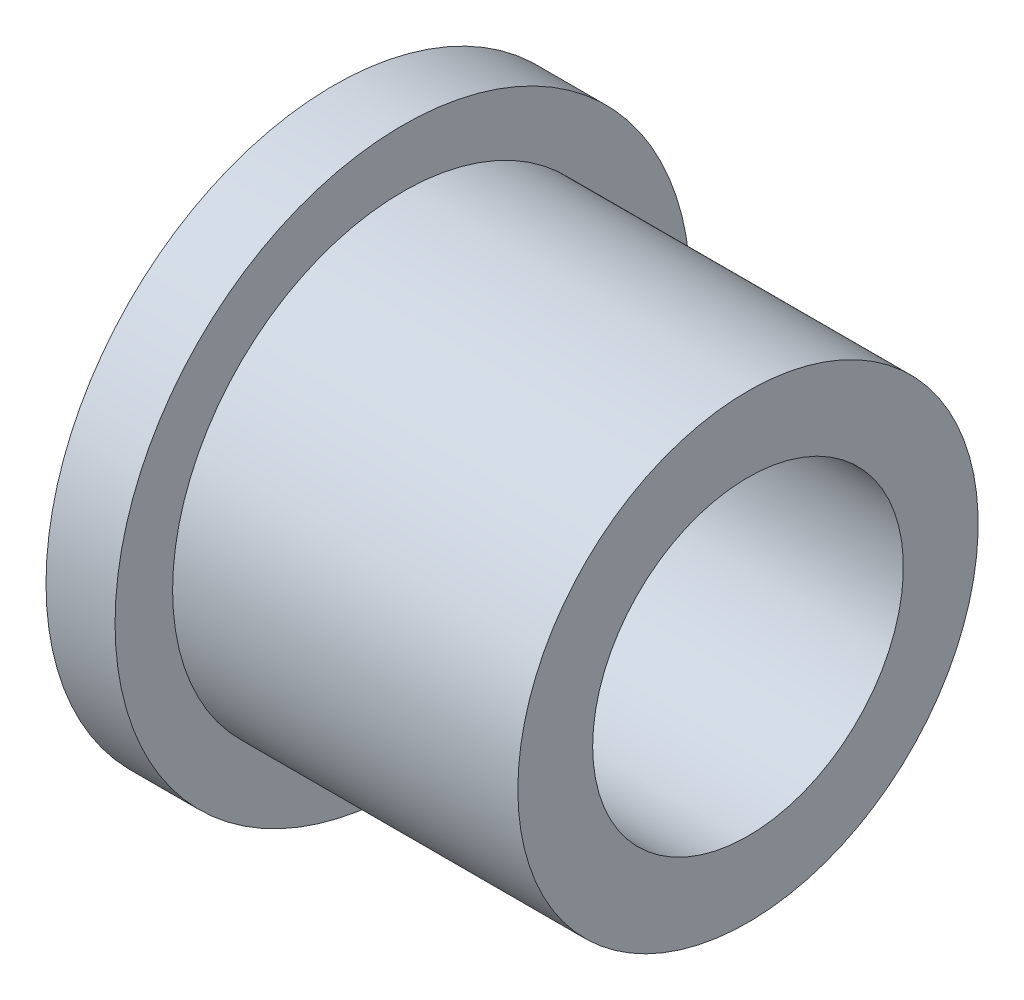
SolidWorks part; units mm, degrees
ref_plane "Front Plane" through (0, 0, 0) normal (0, 0, 1) x (1, 0, 0)
ref_plane "Top Plane" through (0, 0, 0) normal (0, 1, 0) x (1, 0, 0)
ref_plane "Right Plane" through (0, 0, 0) normal (1, 0, 0) x (0, 0, -1)
sketch "Sketch1" plane through (0, 0, 0) normal (0, 0, 1) x (1, 0, 0)
  line L0 (0, -16.586) -> (0, 16.586) construction
  line L1 (-30.377, 0) -> (30.377, 0) construction
  line L2 (0, 8.5725) -> (0, 12.7)
  line L3 (0, 12.7) -> (-19.05, 12.7)
  line L4 (-19.05, 12.7) -> (-19.05, 15.875)
  line L5 (-19.05, 15.875) -> (-22.86, 15.875)
  line L6 (-22.86, 15.875) -> (-22.86, 8.5725)
  line L7 (-22.86, 8.5725) -> (0, 8.5725)
  dimension "D1" = 19.05
  dimension "D2" = 22.86
  dimension "D3" = 17.145
  dimension "D4" = 31.75
  dimension "D5" = 25.4
revolve "Revolve1" add sketch "Sketch1" angle 360 about L1
